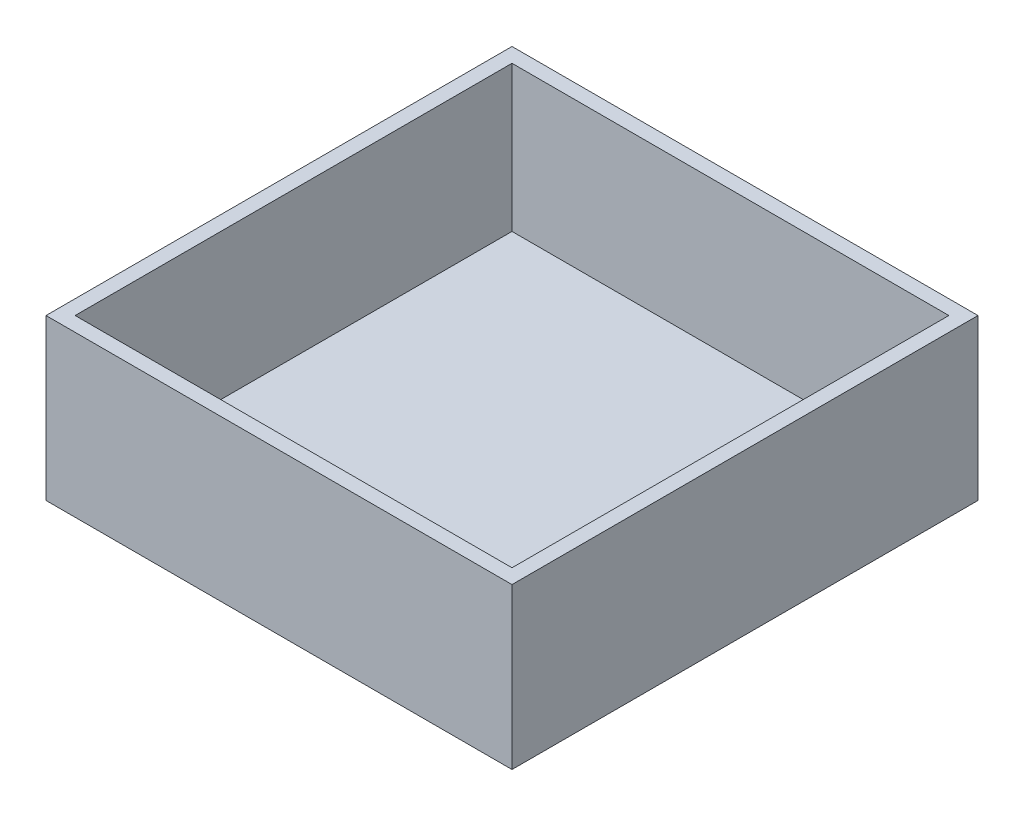
SolidWorks part; units mm, degrees
material "ABS"
ref_plane "Plan de face" through (0, 0, 0) normal (0, 0, 1) x (1, 0, 0)
ref_plane "Plan de dessus" through (0, 0, 0) normal (0, 1, 0) x (1, 0, 0)
ref_plane "Plan de droite" through (0, 0, 0) normal (1, 0, 0) x (0, 0, -1)
sketch "Esquisse1" plane through (0, 0, 0) normal (0, 1, 0) x (1, 0, 0)
  line L1 (-75, -75) -> (75, -75)
  line L2 (-75, -75) -> (-75, 75)
  line L3 (-75, 75) -> (75, 75)
  line L4 (75, -75) -> (75, 75)
  point P4 (0, 75)
  point P6 (-75, 0)
  dimension "D1" = 150
  dimension "D2" = 150
extrude "Boss.-Extru.1" add sketch "Esquisse1" along normal blind 50
shell "Coque2" thickness 5
